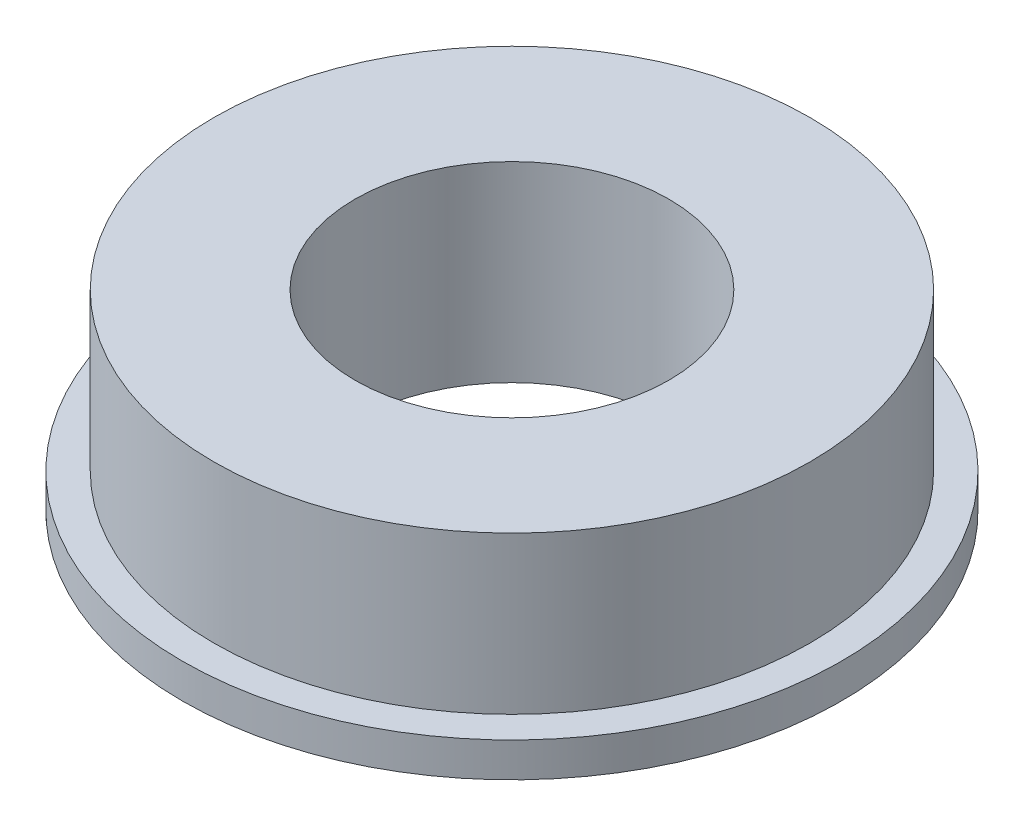
SolidWorks part; units mm, degrees
ref_plane "前视基准面" through (0, 0, 0) normal (0, 0, 1) x (1, 0, 0)
ref_plane "上视基准面" through (0, 0, 0) normal (0, 1, 0) x (1, 0, 0)
ref_plane "右视基准面" through (0, 0, 0) normal (1, 0, 0) x (0, 0, -1)
sketch "草图1" plane through (0, 0, 0) normal (0, 1, 0) x (1, 0, 0)
  circle A0 centre (0, 0) radius 5
  circle A1 centre (0, 0) radius 10.5
  dimension "D1" = 10
  dimension "D2" = 21
extrude "凸台-拉伸1" add sketch "草图1" along normal blind 1.1
sketch "草图2" plane through (0, 1.1, 0) normal (0, 1, 0) x (1, 0, 0)
  circle A0 centre (0, 0) radius 5
  circle A1 centre (0, 0) radius 9.5
  dimension "D1" = 10
  dimension "D2" = 19
extrude "凸台-拉伸2" add sketch "草图2" along normal blind 5
